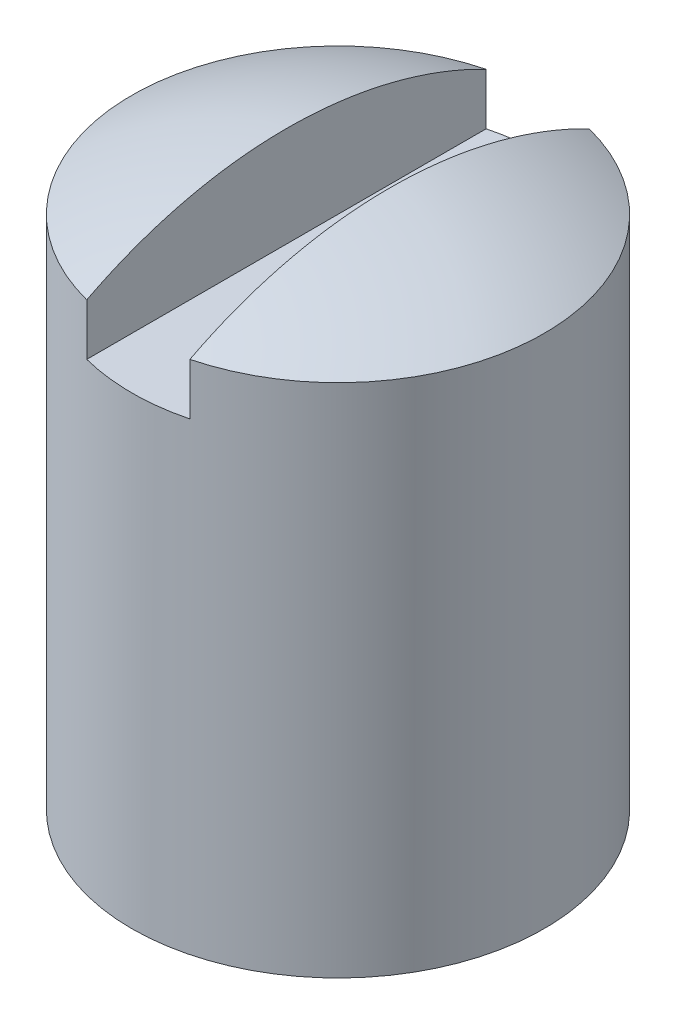
SolidWorks part; units mm, degrees
ref_plane "前基準面" through (0, 0, 0) normal (0, 0, 1) x (1, 0, 0)
ref_plane "上基準面" through (0, 0, 0) normal (0, 1, 0) x (1, 0, 0)
ref_plane "右基準面" through (0, 0, 0) normal (1, 0, 0) x (0, 0, -1)
sketch "草圖1" plane through (0, 0, 0) normal (0, 0, 1) x (1, 0, 0)
  line L0 (-4, 12.5) -> (-4, 2.5)
  line L1 (-4, 2.5) -> (-1.8349, 1.25)
  line L2 (0, 0) -> (0, 16.3404) construction
  line L3 (-1.8349, 1.25) -> (0, 1.25)
  line L4 (-1.8349, 1.25) -> (0, 0.1906) construction
  line L5 (0, 1.25) -> (0, 13.5)
  arc A0 (0, 13.5) -> (-4, 12.5) centre (0, 5) ccw
  dimension "D1" = 1.25
  dimension "D2" = 60
  dimension "D3" = 8
  dimension "D4" = 2.5
  dimension "D5" = 10
  dimension "D6" = 1
revolve "旋轉1" add sketch "草圖1" angle 360 about L2
cosmetic thread "裝飾螺紋線1" parameters "D2"=6.8
sketch "草圖2" plane through (0, 0, 0) normal (0, 0, 1) x (1, 0, 0)
  line L0 (0, 0) -> (0, 11.5) construction
  line L1 (-1, 13.9095) -> (1, 13.9095)
  line L2 (-1, 13.9095) -> (-1, 11.5)
  line L3 (-1, 11.5) -> (1, 11.5)
  line L4 (1, 13.9095) -> (1, 11.5)
  line L5 (4, 12.5) -> (-4, 12.5) construction
  dimension "D1" = 1
  dimension "D2" = 2
extrude "除料-伸長1" cut sketch "草圖2" against normal mid plane 10
sketch "草圖3" plane through (0, 0, 0) normal (0, 0, 1) x (1, 0, 0)
  line L0 (1.8349, 1.25) -> (4, 2.5) construction
  line L1 (1.8349, 1.25) -> (4, 2.5)
